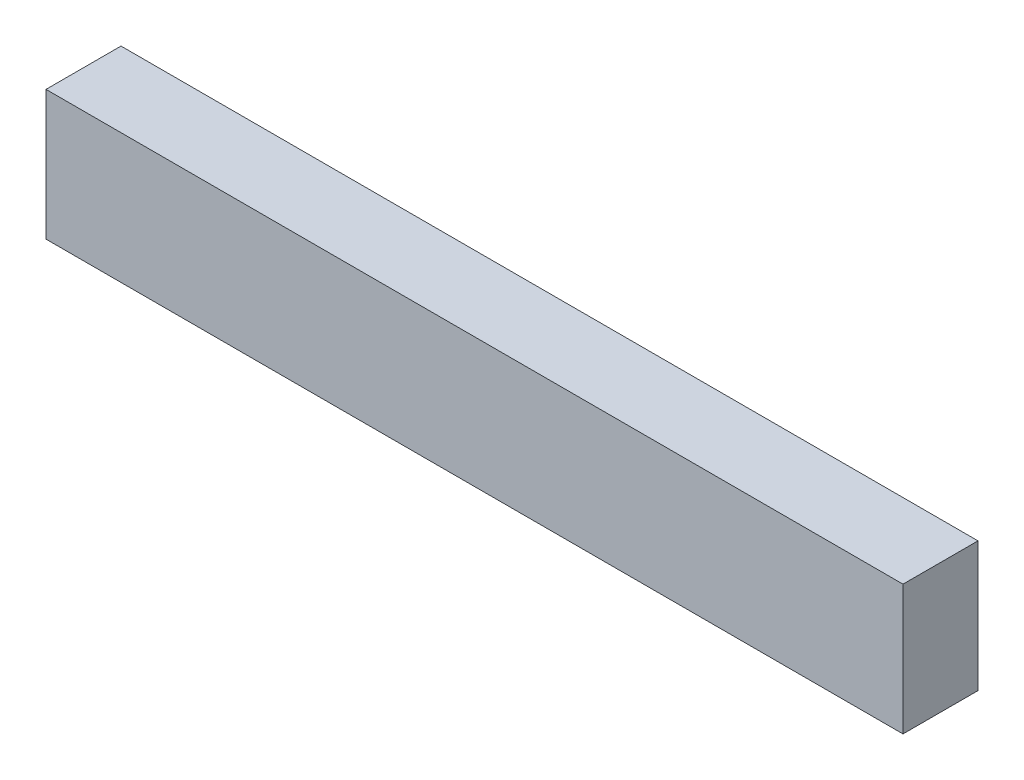
SolidWorks part; units mm, degrees
ref_plane "Front Plane" through (0, 0, 0) normal (0, 0, 1) x (1, 0, 0)
ref_plane "Top Plane" through (0, 0, 0) normal (0, 1, 0) x (1, 0, 0)
ref_plane "Right Plane" through (0, 0, 0) normal (1, 0, 0) x (0, 0, -1)
sketch "Sketch1" plane through (0, 0, 0) normal (0, 0, 1) x (1, 0, 0)
  line L0 (-79.2368, 46.33) -> (-32.2955, 46.33) construction
  line L1 (-16.7755, 46.13) -> (66.0645, 46.13)
  line L2 (-16.7755, 46.13) -> (-16.7755, 33.59)
  line L3 (-16.7755, 33.59) -> (66.0645, 33.59)
  line L4 (66.0645, 46.13) -> (66.0645, 33.59)
  line L5 (66.2645, 46.33) -> (66.2645, 33.39) construction
  line L6 (66.2645, 33.39) -> (-16.9755, 33.39) construction
  line L7 (-16.9755, 33.39) -> (-16.9755, 46.33) construction
  point P4 (-55.7662, 46.33)
  dimension "D1" = 0.2
  dimension "D2" = 0.2
  dimension "D3" = 0.2
  dimension "D4" = 0.2
extrude "Boss-Extrude1" add sketch "Sketch1" along normal blind 7.25
shell "Shell1" thickness 0.5
equation "\"D2@Sketch1\"=\"D1@Sketch1\""
equation "\"D3@Sketch1\"=\"D1@Sketch1\""
equation "\"D4@Sketch1\"=\"D1@Sketch1\""
